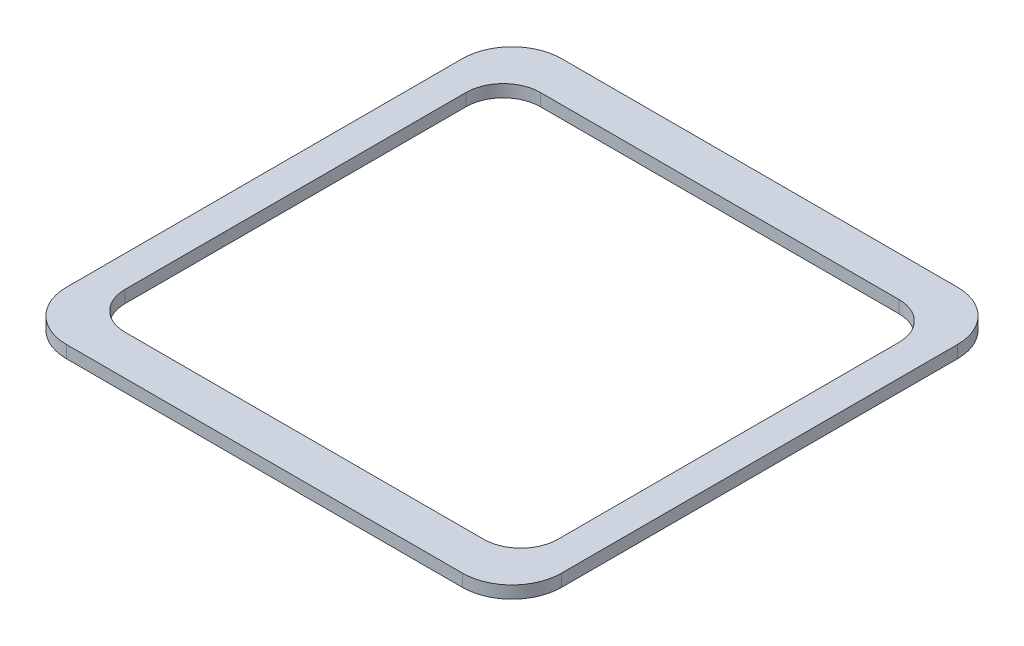
SolidWorks part; units mm, degrees
ref_plane "Front Plane" through (0, 0, 0) normal (0, 0, 1) x (1, 0, 0)
ref_plane "Top Plane" through (0, 0, 0) normal (0, 1, 0) x (1, 0, 0)
ref_plane "Right Plane" through (0, 0, 0) normal (1, 0, 0) x (0, 0, -1)
sketch "Sketch2" plane through (0, 49.3427, 0) normal (0, 1, 0) x (1, 0, 0)
  line L23 (36.6125, 86.6466) -> (-64.9875, 86.6466)
  line L24 (49.3125, -27.6534) -> (49.3125, 73.9466)
  line L25 (-60.1797, -30.1159) -> (31.8047, -30.1159)
  line L26 (-60.1797, -30.1159) -> (31.8047, -30.1159)
  line L32 (-64.9875, -40.3534) -> (36.6125, -40.3534) construction
  line L33 (-77.6875, 73.9466) -> (-77.6875, -27.6534) construction
  line L34 (-64.9875, -40.3534) -> (36.6125, -40.3534)
  line L35 (-77.6875, 73.9466) -> (-77.6875, -27.6534)
  line L66 (31.8047, 76.4092) -> (-60.1797, 76.4092)
  line L69 (31.8047, 76.4092) -> (-60.1797, 76.4092)
  line L104 (41.3284, -20.5922) -> (41.3284, 66.8854)
  line L107 (41.3284, -20.5922) -> (41.3284, 66.8854)
  line L119 (-69.7035, 66.8854) -> (-69.7035, 23.1466)
  line L120 (-69.7035, 66.8854) -> (-69.7035, 23.1466)
  line L121 (-69.7035, 23.1466) -> (-69.7035, -20.5922)
  line L122 (-69.7035, 23.1466) -> (-69.7035, -20.5922)
  arc A2 (49.3125, 73.9466) -> (36.6125, 86.6466) centre (36.6125, 73.9466) ccw
  arc A17 (-64.9875, 86.6466) -> (-77.6875, 73.9466) centre (-64.9875, 73.9466) ccw
  arc A21 (-69.7035, -20.5922) -> (-60.1797, -30.1159) centre (-60.1797, -20.5922) ccw
  arc A25 (-69.7035, -20.5922) -> (-60.1797, -30.1159) centre (-60.1797, -20.5922) ccw
  arc A29 (36.6125, -40.3534) -> (49.3125, -27.6534) centre (36.6125, -27.6534) ccw construction
  arc A30 (-77.6875, -27.6534) -> (-64.9875, -40.3534) centre (-64.9875, -27.6534) ccw construction
  arc A31 (36.6125, -40.3534) -> (49.3125, -27.6534) centre (36.6125, -27.6534) ccw
  arc A32 (-77.6875, -27.6534) -> (-64.9875, -40.3534) centre (-64.9875, -27.6534) ccw
  arc A49 (31.8047, -30.1159) -> (41.3284, -20.5922) centre (31.8047, -20.5922) ccw
  arc A50 (31.8047, -30.1159) -> (41.3284, -20.5922) centre (31.8047, -20.5922) ccw
  arc A51 (41.3284, 66.8854) -> (31.8047, 76.4092) centre (31.8047, 66.8854) ccw
  arc A52 (41.3284, 66.8854) -> (31.8047, 76.4092) centre (31.8047, 66.8854) ccw
  arc A53 (-60.1797, 76.4092) -> (-69.7035, 66.8854) centre (-60.1797, 66.8854) ccw
  arc A54 (-60.1797, 76.4092) -> (-69.7035, 66.8854) centre (-60.1797, 66.8854) ccw
  dimension "D1" = 1.5875
extrude "MainBody" add sketch "Sketch2" along normal blind 3.175
equation "\"ClampDepth\"= 3 / 8in"
equation "\"D1@Sketch2\"=0.0625"
